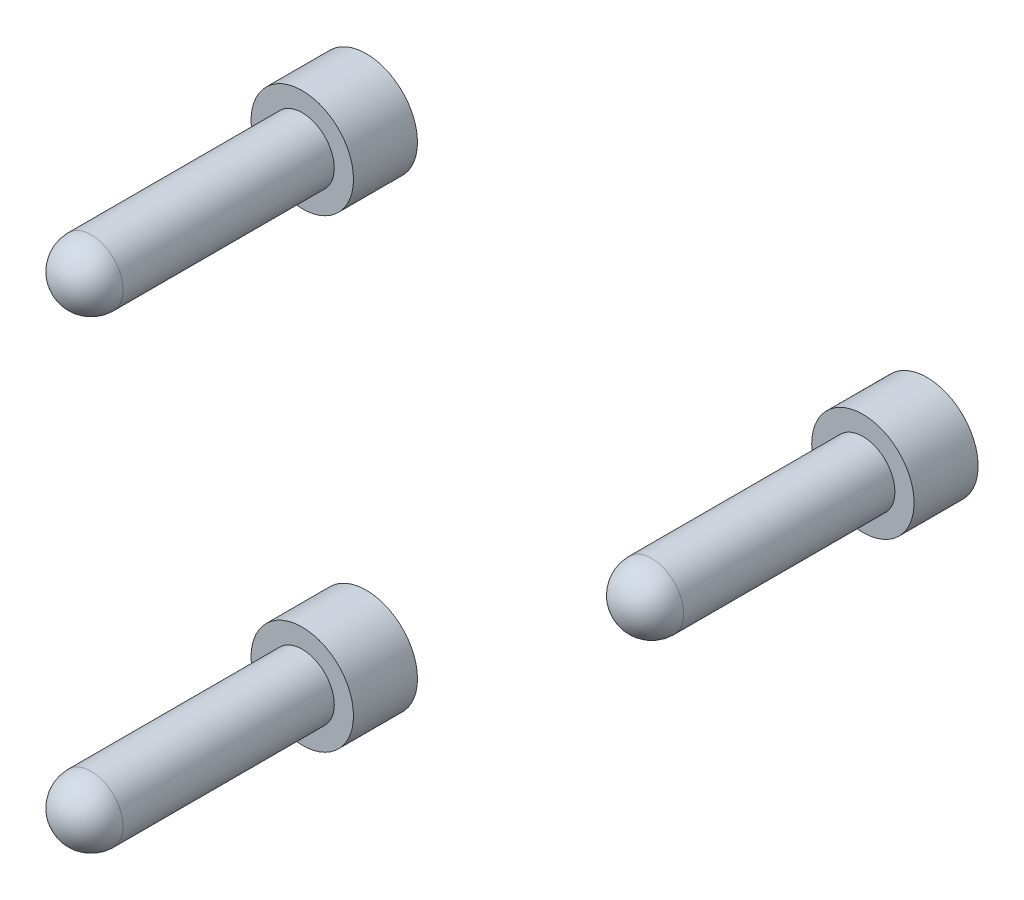
SolidWorks part; units mm, degrees
ref_plane "前基準面" through (0, 0, 0) normal (0, 0, 1) x (1, 0, 0)
ref_plane "上基準面" through (0, 0, 0) normal (0, 1, 0) x (1, 0, 0)
ref_plane "右基準面" through (0, 0, 0) normal (1, 0, 0) x (0, 0, -1)
sketch "草圖1" plane through (0, 0, 0) normal (0, 0, 1) x (1, 0, 0)
  line L0 (0, 26.9) -> (0, -26.9) construction
  line L1 (-34.9, 26.9) -> (34.9, 26.9) construction
  line L2 (-34.9, 26.9) -> (-34.9, -26.9) construction
  line L3 (-34.9, -26.9) -> (34.9, -26.9) construction
  line L4 (34.9, 26.9) -> (34.9, -26.9) construction
  line L5 (-34.9, 26.9) -> (34.9, -26.9) construction
  line L6 (-34.9, -26.9) -> (34.9, 26.9) construction
  circle A0 centre (-21.9, 16.9) radius 4
  circle A1 centre (-21.9, -19.4) radius 4
  circle A2 centre (21.9, 16.9) radius 4
  point P0 (0, 0)
  dimension "D5" = 8
  dimension "D6" = 8
  dimension "D1" = 69.8
  dimension "D2" = 53.8
  dimension "D3" = 10
  dimension "D4" = 13
  dimension "D7" = 7.5
extrude "填料-伸長1" add sketch "草圖1" along normal blind 5
sketch "草圖2" plane through (0, 0, 5) normal (0, 0, 1) x (1, 0, 0)
  circle A0 centre (-21.9, 16.9) radius 2.5
  circle A1 centre (21.9, 16.9) radius 2.5
  circle A2 centre (-21.9, -19.4) radius 2.5
  dimension "D1" = 5
  dimension "D2" = 5
  dimension "D3" = 5
extrude "填料-伸長2" add sketch "草圖2" along normal blind 19
ref_plane "平面1" through (-24.9, 0, 0) normal (1, 0, 0) x (0, 0, -1)
fillet "圓角4" radius 2.5 1 edges at (-19.4, 16.9, 24)
fillet "圓角5" radius 2.5 1 edges at (-19.4, -19.4, 24)
fillet "圓角6" radius 2.5 1 edges at (24.4, 16.9, 24)
